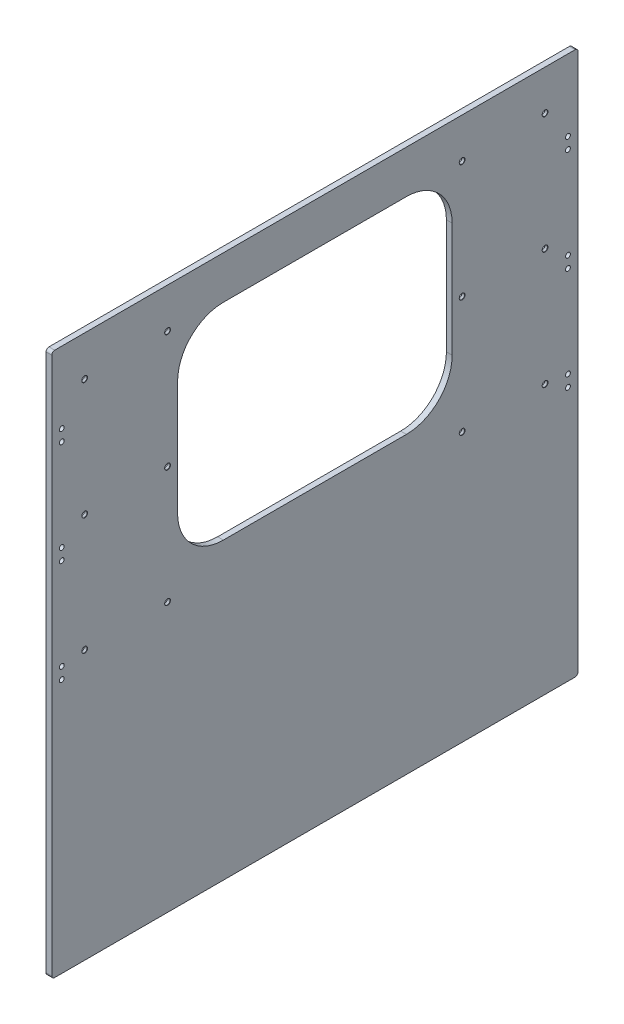
SolidWorks part; units mm, degrees
material "PE High Density"
ref_plane "Front Plane" through (0, 0, 0) normal (0, 0, 1) x (1, 0, 0)
ref_plane "Top Plane" through (0, 0, 0) normal (0, 1, 0) x (1, 0, 0)
ref_plane "Right Plane" through (0, 0, 0) normal (1, 0, 0) x (0, 0, -1)
sketch "Sketch1" plane through (0, 0, 0) normal (1, 0, 0) x (0, 0, -1)
  line L0 (6.35, 0) -> (1162.05, 0)
  line L1 (0, 6.35) -> (0, 1200.15)
  line L2 (1168.4, 6.35) -> (1168.4, 1200.15)
  line L3 (6.35, 1206.5) -> (1162.05, 1206.5)
  line L4 (381, 1111.25) -> (787.4, 1111.25)
  line L5 (279.4, 1009.65) -> (279.4, 755.65)
  line L6 (889, 1009.65) -> (889, 755.65)
  line L7 (381, 654.05) -> (787.4, 654.05)
  line L8 (279.4, 755.65) -> (0, 755.65) construction
  line L9 (889, 755.65) -> (1168.4, 755.65) construction
  arc A0 (0, 6.35) -> (6.35, 0) centre (6.35, 6.35) ccw
  arc A1 (1162.05, 0) -> (1168.4, 6.35) centre (1162.05, 6.35) ccw
  arc A2 (1168.4, 1200.15) -> (1162.05, 1206.5) centre (1162.05, 1200.15) ccw
  arc A3 (6.35, 1206.5) -> (0, 1200.15) centre (6.35, 1200.15) ccw
  arc A4 (279.4, 755.65) -> (381, 654.05) centre (381, 755.65) ccw
  arc A5 (889, 755.65) -> (787.4, 654.05) centre (787.4, 755.65) cw
  arc A6 (787.4, 1111.25) -> (889, 1009.65) centre (787.4, 1009.65) cw
  arc A7 (279.4, 1009.65) -> (381, 1111.25) centre (381, 1009.65) cw
  point P11 (0, 0)
  point P14 (1168.4, 0)
  point P17 (1168.4, 1206.5)
  point P20 (0, 1206.5)
  point P23 (279.4, 654.05)
  point P28 (889, 1111.25)
  point P31 (279.4, 1111.25)
  dimension "D7" = 6.35
  dimension "D8" = 101.6
  dimension "D1" = 1168.4
  dimension "D2" = 609.6
  dimension "D4" = 1206.5
  dimension "D5" = 654.05
  dimension "D6" = 457.2
extrude "Boss-Extrude1" add sketch "Sketch1" along normal blind 12.7
hole_wizard "CSK for 1/4 Flat Head Machine Screw1" positions "Sketch2" profile "Sketch3" countersink size "1/4" standard "ANSI Inch" end condition through all
sketch "Sketch2" plane through (12.7, 0, 0) normal (1, 0, 0) x (0, 0, -1)
  line L3 (1162.05, 1206.5) -> (6.35, 1206.5) construction
  line L4 (279.4, 1009.65) -> (279.4, 755.65) construction
  line L5 (889, 755.65) -> (889, 1009.65) construction
  point P0 (73.025, 1117.6)
  point P2 (73.025, 857.25)
  point P4 (73.025, 596.9)
  point P6 (257.175, 1117.6)
  point P8 (257.175, 857.25)
  point P10 (257.175, 596.9)
  point P12 (911.225, 1117.6)
  point P14 (911.225, 857.25)
  point P16 (911.225, 596.9)
  point P18 (1095.375, 1117.6)
  point P20 (1095.375, 857.25)
  point P22 (1095.375, 596.9)
  dimension "D1" = 184.15
  dimension "D2" = 184.15
  dimension "D3" = 22.225
  dimension "D4" = 22.225
  dimension "D5" = 88.9
  dimension "D6" = 260.35
  dimension "D7" = 260.35
sketch "Sketch3" plane through (12.7, 1117.6, -73.025) normal (0, 1, 0) x (0, 0, -1)
  line L0 (0, 0) -> (0, 12.7)
  line L1 (0, 12.7) -> (3.3782, 12.7)
  line L2 (3.3782, 12.7) -> (3.3782, 4.5369)
  line L3 (3.3782, 4.5369) -> (6.4389, 1.016)
  line L4 (6.4389, 1.016) -> (6.4389, 0)
  line L6 (6.4389, 0) -> (0, 0)
  line L7 (-3.3782, 4.5369) -> (-6.4389, 1.016) construction
  line L11 (0, -6.35) -> (0, 107.95) construction
  dimension "Thru Hole Dia." = 6.7564
  dimension "Thru Hole Depth" = 12.7
  dimension "C'Sink Dia." = 12.8778
  dimension "C'Sink Angle" = 82
  dimension "Head Clearance" = 1.016
hole_wizard "27/64 (0.42188) Diameter Hole1" positions "Sketch4" profile "Sketch5" hole size "27/64" standard "ANSI Inch" end condition through all
sketch "Sketch4" plane through (12.7, 0, 0) normal (1, 0, 0) x (0, 0, -1)
  line L0 (0, 1200.15) -> (0, 6.35) construction
  line L1 (1168.4, 6.35) -> (1168.4, 1200.15) construction
  line L2 (1162.05, 1206.5) -> (6.35, 1206.5) construction
  point P0 (22.225, 1047.75)
  point P2 (22.225, 590.55)
  point P4 (1146.175, 1047.75)
  point P6 (1146.175, 590.55)
  point P8 (1146.175, 819.15)
  point P10 (22.225, 819.15)
  point P24 (22.225, 1022.35)
  point P26 (22.225, 793.75)
  point P28 (22.225, 565.15)
  point P30 (1146.175, 1022.35)
  point P32 (1146.175, 793.75)
  point P34 (1146.175, 565.15)
  dimension "D1" = 228.6
  dimension "D2" = 228.6
  dimension "D3" = 22.225
  dimension "D4" = 22.225
  dimension "D5" = 158.75
  dimension "D6" = 25.4
  dimension "D7" = 25.4
  dimension "D8" = 25.4
sketch "Sketch5" plane through (12.7, 1047.75, -22.225) normal (0, 1, 0) x (0, 0, -1)
  line L0 (0, 0) -> (0, 12.7)
  line L1 (0, 12.7) -> (5.3579, 12.7)
  line L2 (5.3579, 12.7) -> (5.3579, 0)
  line L5 (5.3579, 0) -> (0, 0)
  line L11 (0, -6.35) -> (0, 107.95) construction
  dimension "Thru Hole Dia." = 10.7158
  dimension "Thru Hole Depth" = 12.7
